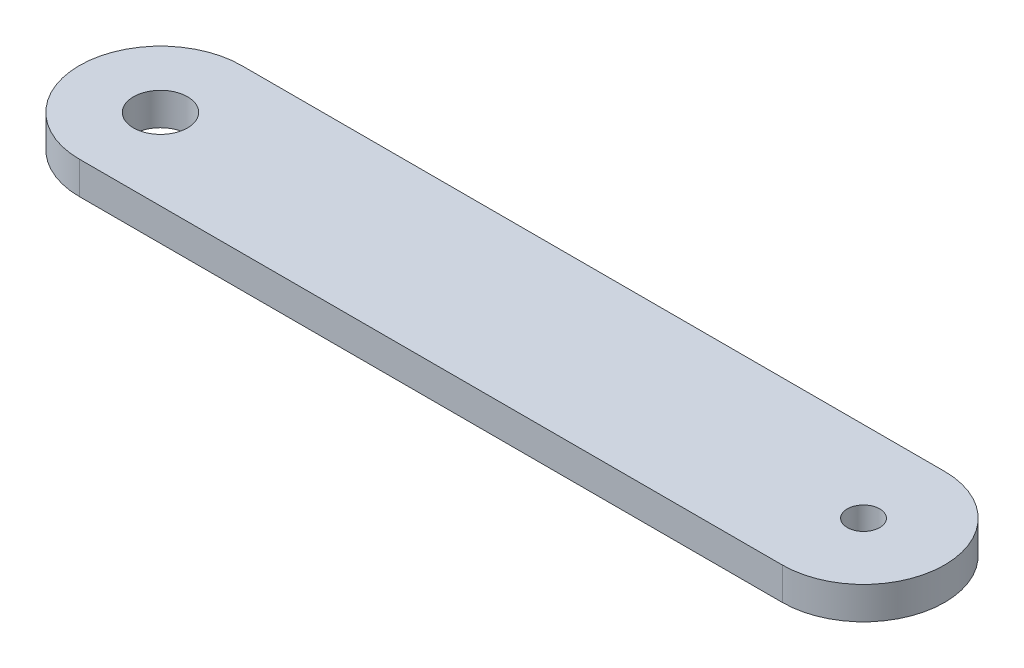
SolidWorks part; units mm, degrees
ref_plane "Front Plane" through (0, 0, 0) normal (0, 0, 1) x (1, 0, 0)
ref_plane "Top Plane" through (0, 0, 0) normal (0, 1, 0) x (1, 0, 0)
ref_plane "Right Plane" through (0, 0, 0) normal (1, 0, 0) x (0, 0, -1)
sketch "Sketch2" plane through (0, 0, 0) normal (0, 1, 0) x (1, 0, 0)
  line L1 (-6.5, 28.5) -> (123.5, 28.5)
  line L3 (-6.5, -1.5) -> (123.5, -1.5)
  arc A0 (-6.5, 28.5) -> (-6.5, -1.5) centre (-6.5, 13.5) ccw
  circle A1 centre (-6.5, 13.5) radius 5
  arc A2 (123.5, -1.5) -> (123.5, 28.5) centre (123.5, 13.5) ccw
  circle A3 centre (123.5, 13.5) radius 3
extrude "Boss-Extrude1" add sketch "Sketch2" along normal blind 6
